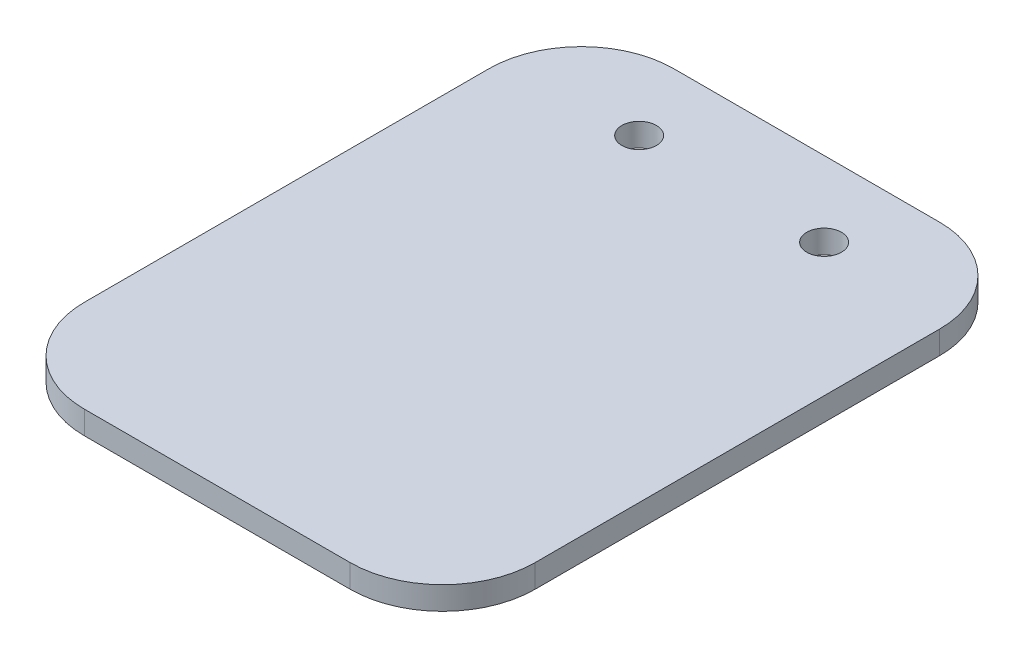
SolidWorks part; units mm, degrees
ref_plane "Front Plane" through (0, 0, 0) normal (0, 0, 1) x (1, 0, 0)
ref_plane "Top Plane" through (0, 0, 0) normal (0, 1, 0) x (1, 0, 0)
ref_plane "Right Plane" through (0, 0, 0) normal (1, 0, 0) x (0, 0, -1)
sketch "Sketch1" plane through (0, 0, 0) normal (0, 1, 0) x (1, 0, 0)
  line L0 (0, 25.5) -> (39, 25.5) construction
  line L1 (8, 0) -> (31, 0)
  line L2 (0, 8) -> (0, 43)
  line L3 (8, 51) -> (31, 51)
  line L4 (39, 8) -> (39, 43)
  line L5 (19.5, 51) -> (19.5, 0) construction
  circle A0 centre (27.5, 44.5) radius 1.5
  circle A1 centre (11.5, 44.5) radius 1.5
  arc A2 (8, 0) -> (0, 8) centre (8, 8) cw
  arc A3 (31, 0) -> (39, 8) centre (31, 8) ccw
  arc A4 (31, 51) -> (39, 43) centre (31, 43) cw
  arc A5 (0, 43) -> (8, 51) centre (8, 43) cw
  point P15 (0, 0)
  point P18 (39, 0)
  point P23 (0, 51)
  dimension "D3" = 3
  dimension "D6" = 8
  dimension "D1" = 39
  dimension "D2" = 51
  dimension "D4" = 6.5
  dimension "D5" = 8
extrude "Boss-Extrude1" add sketch "Sketch1" along normal blind 2
